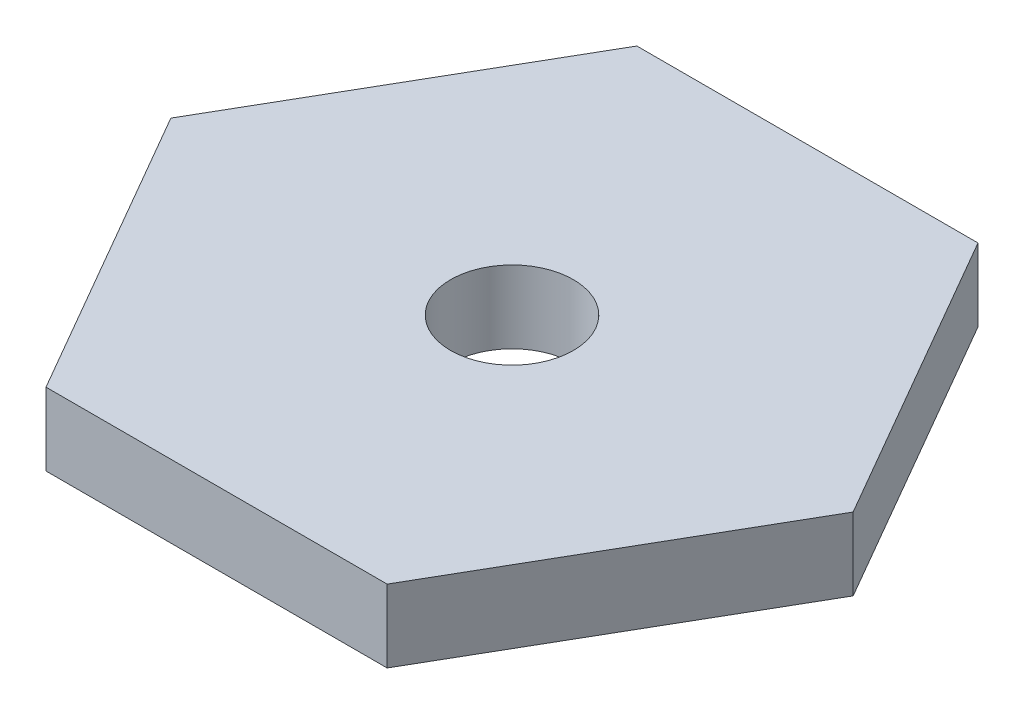
SolidWorks part; units mm, degrees
ref_plane "Front Plane" through (0, 0, 0) normal (0, 0, 1) x (1, 0, 0)
ref_plane "Top Plane" through (0, 0, 0) normal (0, 1, 0) x (1, 0, 0)
ref_plane "Right Plane" through (0, 0, 0) normal (1, 0, 0) x (0, 0, -1)
sketch "Sketch1" plane through (0, 0, 0) normal (0, 1, 0) x (1, 0, 0)
  line L1 (26.4571, 45.825) -> (-26.4571, 45.825)
  line L2 (-26.4571, 45.825) -> (-52.9142, 0)
  line L3 (-52.9142, 0) -> (-26.4571, -45.825)
  line L4 (-26.4571, -45.825) -> (26.4571, -45.825)
  line L5 (26.4571, -45.825) -> (52.9142, 0)
  line L6 (52.9142, 0) -> (26.4571, 45.825)
  circle A0 centre (0, 0) radius 45.825 construction
  dimension "D1" = 91.65
extrude "Boss-Extrude1" add sketch "Sketch1" along normal blind 11.27
sketch "Sketch2" plane through (0, 11.27, 0) normal (0, 1, 0) x (1, 0, 0)
  circle A0 centre (0, 0) radius 9.525
  dimension "D1" = 19.05
extrude "Cut-Extrude1" cut sketch "Sketch2" against normal through all
